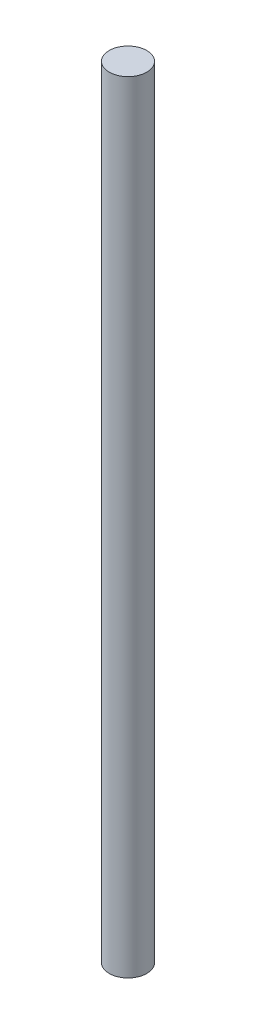
SolidWorks part; units mm, degrees
ref_plane "Front" through (0, 0, 0) normal (0, 0, 1) x (1, 0, 0)
ref_plane "Top" through (0, 0, 0) normal (0, 1, 0) x (1, 0, 0)
ref_plane "Right" through (0, 0, 0) normal (1, 0, 0) x (0, 0, -1)
sketch "Sketch1" plane through (0, 0, 0) normal (0, 1, 0) x (1, 0, 0)
  circle A0 centre (0, 0) radius 1.9
  dimension "D1" = 3.8
extrude "Boss-Extrude1" add sketch "Sketch1" along normal blind 79
